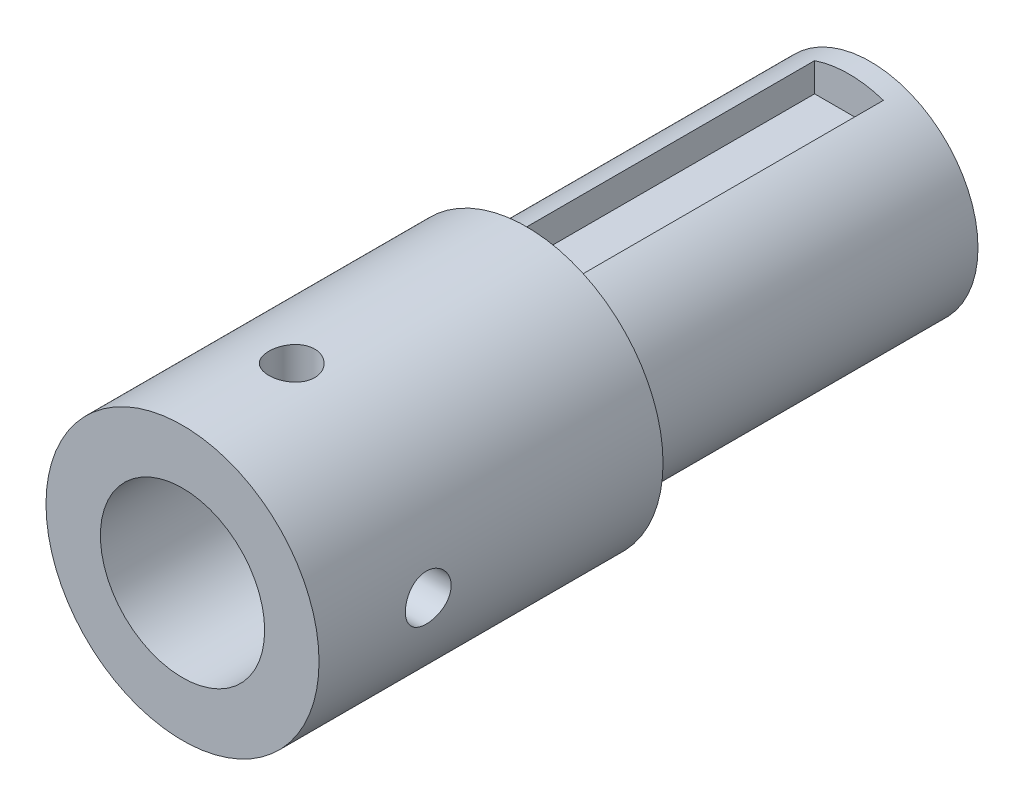
SolidWorks part; units mm, degrees
ref_plane "Front" through (0, 0, 0) normal (0, 0, 1) x (1, 0, 0)
ref_plane "Top" through (0, 0, 0) normal (0, 1, 0) x (1, 0, 0)
ref_plane "Right" through (0, 0, 0) normal (1, 0, 0) x (0, 0, -1)
sketch "Sketch1" plane through (0, 0, 0) normal (0, 0, 1) x (1, 0, 0)
  circle A0 centre (0, 0) radius 12.5
  dimension "D1" = 25
extrude "Boss-Extrude1" add sketch "Sketch1" along normal blind 40
ref_plane "Plane1" through (0, 12.5, 0) normal (0, 1, 0) x (1, 0, 0)
sketch "Sketch2" plane through (0, 12.5, 0) normal (0, 1, 0) x (1, 0, 0)
  line L0 (0, 0) -> (0, -40) construction
  line L1 (12.5, 0) -> (-12.5, 0) construction
  line L2 (-12.5, -40) -> (12.5, -40) construction
  line L4 (4, -37.5) -> (-4, -37.5)
  line L5 (4, -37.5) -> (4, -2.5)
  line L6 (4, -2.5) -> (-4, -2.5)
  line L7 (-4, -37.5) -> (-4, -2.5)
  line L8 (4, -37.5) -> (-4, -2.5) construction
  line L9 (4, -2.5) -> (-4, -37.5) construction
  point P6 (0, -20)
  dimension "D1" = 8
  dimension "D2" = 35
extrude "Cut-Extrude1" cut sketch "Sketch2" against normal blind 4
sketch "Sketch3" plane through (0, 0, 40) normal (0, 0, 1) x (1, 0, 0)
  circle A0 centre (0, 0) radius 15.875
  dimension "D1" = 31.75
extrude "Boss-Extrude2" add sketch "Sketch3" along normal blind 40
sketch "Sketch5" plane through (0, 0, 80) normal (0, 0, 1) x (1, 0, 0)
  circle A0 centre (0, 0) radius 9.5504
  dimension "D1" = 19.1008
extrude "Cut-Extrude2" cut sketch "Sketch5" against normal blind 25.4
sketch "Sketch6" plane through (0, 0, 0) normal (0, 1, 0) x (1, 0, 0)
  line L0 (0, -80) -> (0, -67.3) construction
  line L1 (-15.875, -80) -> (15.875, -80) construction
  circle A0 centre (0, -67.3) radius 2.665
  dimension "D2" = 5.33
  dimension "D1" = 12.7
extrude "Cut-Extrude3" cut sketch "Sketch6" along normal up to next
pattern_circular "CirPattern1" count 2 over 90 about axis through (0, 0, 80) along (0, 0, 1) of "Cut-Extrude3"
